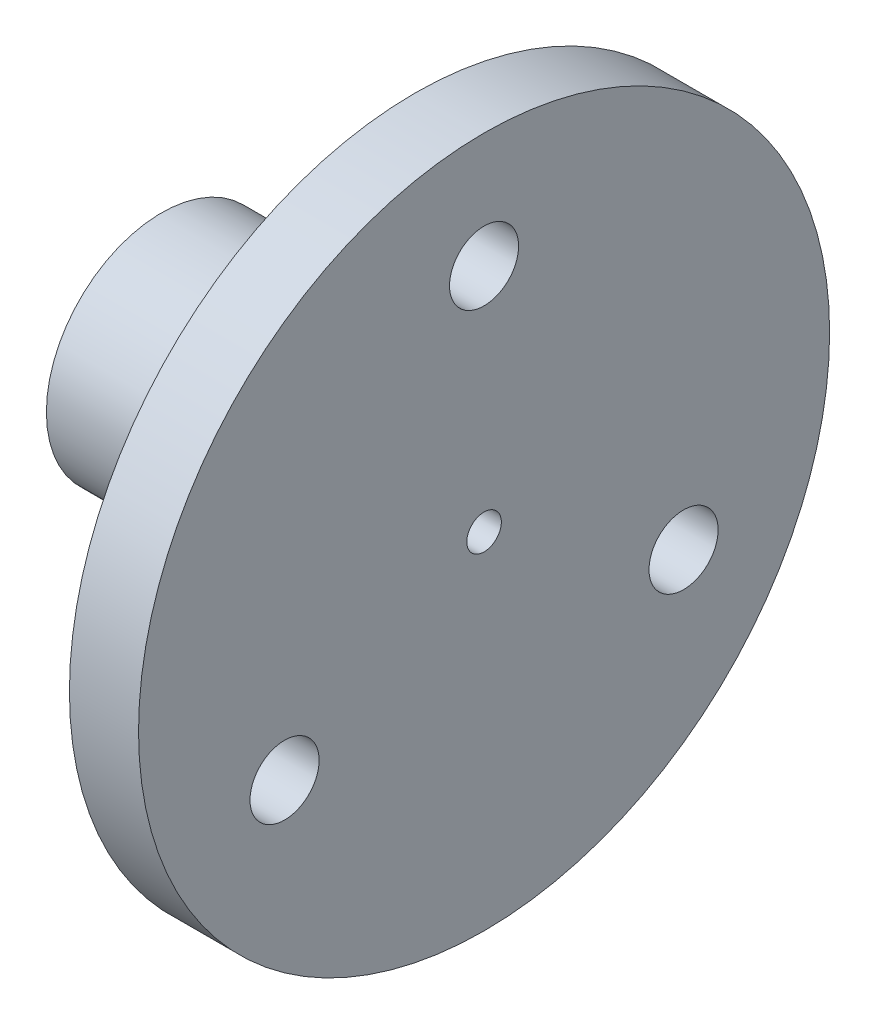
SolidWorks part; units mm, degrees
ref_plane "Front Plane" through (0, 0, 0) normal (0, 0, 1) x (1, 0, 0)
ref_plane "Top Plane" through (0, 0, 0) normal (0, 1, 0) x (1, 0, 0)
ref_plane "Right Plane" through (0, 0, 0) normal (1, 0, 0) x (0, 0, -1)
sketch "Sketch2" plane through (0, 0, 0) normal (0, 0, 1) x (1, 0, 0)
  line L0 (0, 0) -> (14, 0) construction
  line L1 (14, 0) -> (14, 15) construction
  line L2 (14, 15) -> (11, 15)
  line L3 (11, 15) -> (11, 5)
  line L4 (11, 5) -> (0, 5)
  line L5 (0, 0) -> (0, 18.7292) construction
  line L6 (14, 0.75) -> (0, 0.75)
  line L7 (0, 5) -> (0, 0.75)
  line L8 (14, 15) -> (14, 0.75)
  dimension "D1" = 15
  dimension "D2" = 10
  dimension "D3" = 3
  dimension "D4" = 1.5
  dimension "D5" = 14
revolve "Revolve1" add sketch "Sketch2" angle 360 about L0
sketch "Sketch3" plane through (11, 0, 0) normal (-1, 0, 0) x (0, 0, 1)
  line L0 (0, 5) -> (0, 15) construction
  line L1 (0, -7.7) -> (0, 7.7) construction
  circle A0 centre (0, 0) radius 5 construction
  circle A1 centre (0, 0) radius 15 construction
  circle A2 centre (0, 10) radius 1.5
  dimension "D1" = 3
  dimension "D2" = 10
extrude "Cut-Extrude1" cut sketch "Sketch3" against normal blind 10
pattern_circular "CirPattern1" count 3 over 360 about axis through (0, 0, 0) along (1, 0, 0) of "Cut-Extrude1"
